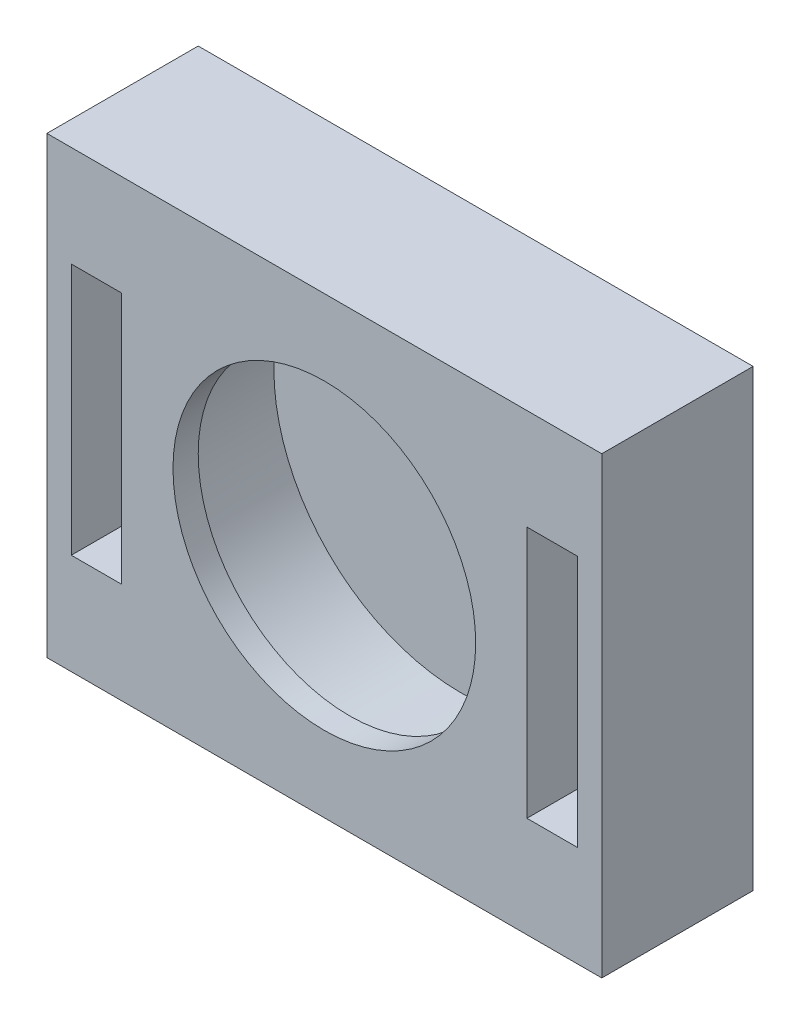
SolidWorks part; units mm, degrees
ref_plane "Front Plane" through (0, 0, 0) normal (0, 0, 1) x (1, 0, 0)
ref_plane "Top Plane" through (0, 0, 0) normal (0, 1, 0) x (1, 0, 0)
ref_plane "Right Plane" through (0, 0, 0) normal (1, 0, 0) x (0, 0, -1)
sketch "Sketch1" plane through (0, 0, 0) normal (0, 0, 1) x (1, 0, 0)
  line L1 (-13.97, -11.43) -> (13.97, -11.43)
  line L2 (-13.97, -11.43) -> (-13.97, 11.43)
  line L3 (-13.97, 11.43) -> (13.97, 11.43)
  line L4 (13.97, -11.43) -> (13.97, 11.43)
  line L5 (-13.97, -11.43) -> (13.97, 11.43) construction
  line L6 (-13.97, 11.43) -> (13.97, -11.43) construction
  point P0 (0, 0)
  dimension "D1" = 27.94
  dimension "D2" = 22.86
extrude "Boss-Extrude1" add sketch "Sketch1" along normal blind 6.35
sketch "Sketch2" plane through (0, 0, 6.35) normal (0, 0, 1) x (1, 0, 0)
  circle A0 centre (0, 0) radius 9.398
  dimension "D1" = 18.796
extrude "Cut-Extrude1" cut sketch "Sketch2" against normal blind 5.588
sketch "Sketch3" plane through (0, 0, 6.35) normal (0, 0, 1) x (1, 0, 0)
  line L1 (-13.97, 11.43) -> (13.97, 11.43)
  line L2 (-13.97, 11.43) -> (-13.97, -11.43)
  line L3 (-13.97, -11.43) -> (13.97, -11.43)
  line L4 (13.97, 11.43) -> (13.97, -11.43)
  circle A0 centre (0, 0) radius 7.62
  dimension "D1" = 27.94
extrude "Boss-Extrude2" add sketch "Sketch3" along normal blind 1.27
sketch "Sketch9" plane through (0, 0, 7.62) normal (0, 0, 1) x (1, 0, 0)
  line L0 (-10.2078, 0) -> (10.2078, 0) construction
  line L1 (10.2078, 0) -> (11.4707, 0) construction
  line L2 (0, -1000) -> (0, 49000) construction
  line L3 (-10.2078, 0) -> (-11.4707, 0) construction
  line L4 (-12.7407, 6.35) -> (-10.2007, 6.35)
  line L5 (12.7407, -6.35) -> (10.2007, -6.35)
  line L6 (12.7407, -6.35) -> (12.7407, 6.35)
  line L7 (12.7407, 6.35) -> (10.2007, 6.35)
  line L8 (10.2007, -6.35) -> (10.2007, 6.35)
  line L9 (12.7407, -6.35) -> (10.2007, 6.35) construction
  line L10 (12.7407, 6.35) -> (10.2007, -6.35) construction
  line L11 (-10.2007, -6.35) -> (-10.2007, 6.35)
  line L12 (-12.7407, -6.35) -> (-10.2007, -6.35)
  line L13 (-12.7407, -6.35) -> (-12.7407, 6.35)
  point P8 (0, 0)
  dimension "D1" = 2.54
  dimension "D2" = 12.7
extrude "Cut-Extrude3" cut sketch "Sketch9" against normal up to surface (7.62 mm away) up to face at (0, 0, 0)
sketch "Sketch10" plane through (0, 11.43, 0) normal (0, 1, 0) x (1, 0, 0)
  line L0 (0, 0) -> (0, -6.35) construction
  line L1 (7.62, -6.35) -> (-7.62, -6.35) construction
